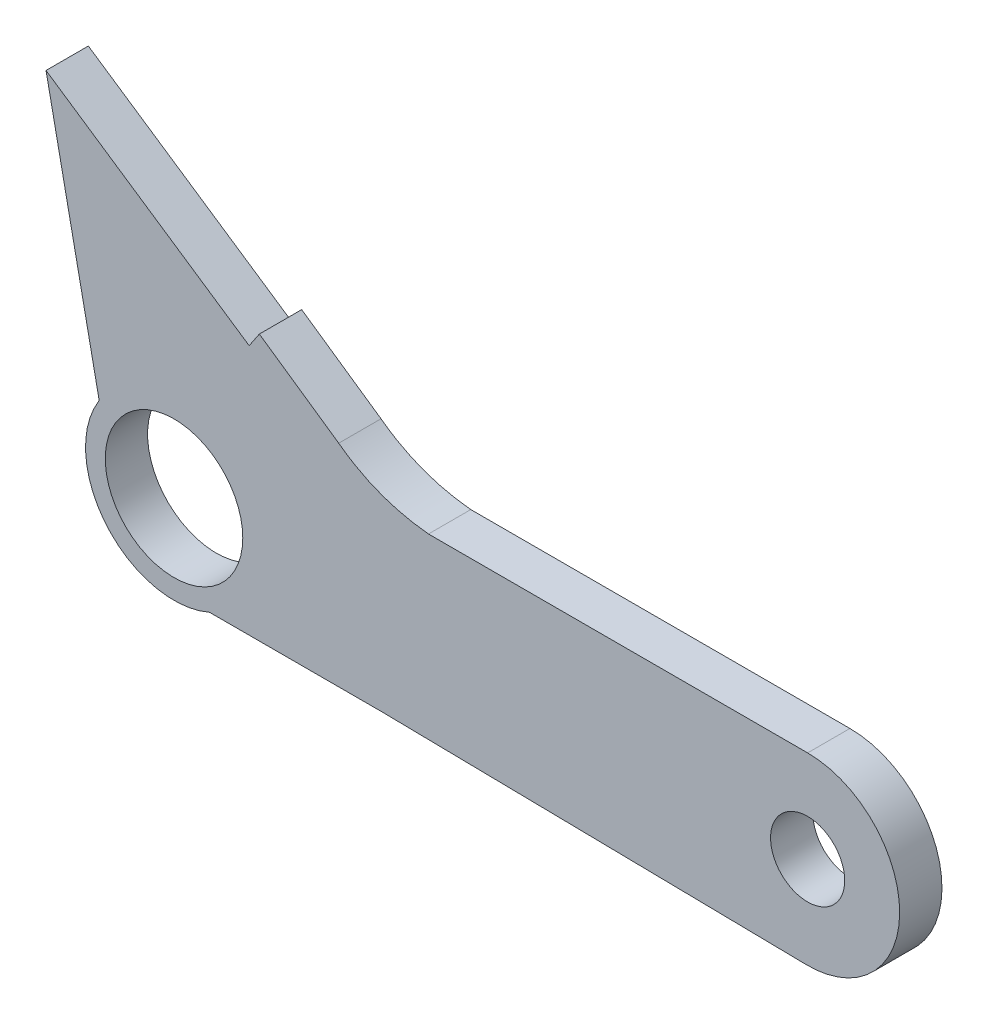
SolidWorks part; units mm, degrees
ref_plane "Front Plane" through (0, 0, 0) normal (0, 0, 1) x (1, 0, 0)
ref_plane "Top Plane" through (0, 0, 0) normal (0, 1, 0) x (1, 0, 0)
ref_plane "Right Plane" through (0, 0, 0) normal (1, 0, 0) x (0, 0, -1)
sketch "Sketch1" plane through (0, 0, 0) normal (0, 0, 1) x (1, 0, 0)
  line L0 (-201.7791, 38.9689) -> (-183.8569, 38.9689)
  line L2 (-203.9423, 30.5877) -> (-183.9958, 30.2692)
  line L4 (-217.3444, 36.6501) -> (-219.8569, 48.9066)
  line L5 (-219.8569, 48.9066) -> (-210.2558, 42.4402)
  line L6 (-210.2558, 42.4402) -> (-209.7733, 43.1565)
  line L7 (-209.7733, 43.1565) -> (-206.0222, 40.564)
  line L14 (-203.9423, 30.5877) -> (-212.1284, 30.5877)
  circle A0 centre (-183.8569, 34.6179) radius 1.7523
  arc A2 (-217.3444, 36.6501) -> (-212.1284, 30.5877) centre (-213.807, 34.4185) ccw
  circle A4 centre (-213.807, 34.4185) radius 3.25
  arc A5 (-183.9958, 30.2692) -> (-183.8569, 38.9689) centre (-183.8569, 34.6179) ccw
  spline S10 degree 3 poles (-206.0222, 40.564) (-204.8456, 39.6827) (-203.4438, 39.1324) (-201.7791, 38.9689) knots 0.24 0.24 0.24 0.24 0.28 0.28 0.28 0.28
  point P5 (0, 0)
  point P8 (-183.8569, 38.9689)
  point P9 (-183.8569, 30.267)
  point P10 (-201.7968, 38.9689)
  point P11 (-203.9423, 30.5877)
  dimension "D2" = 3.5047
  dimension "D3" = 6.5
  dimension "D1" = 36
extrude "Boss-Extrude1" add sketch "Sketch1" along normal blind 2
scale "Scale6" scale about centroid uniform scaling yes scale factor 2.8
scale "Scale4"
